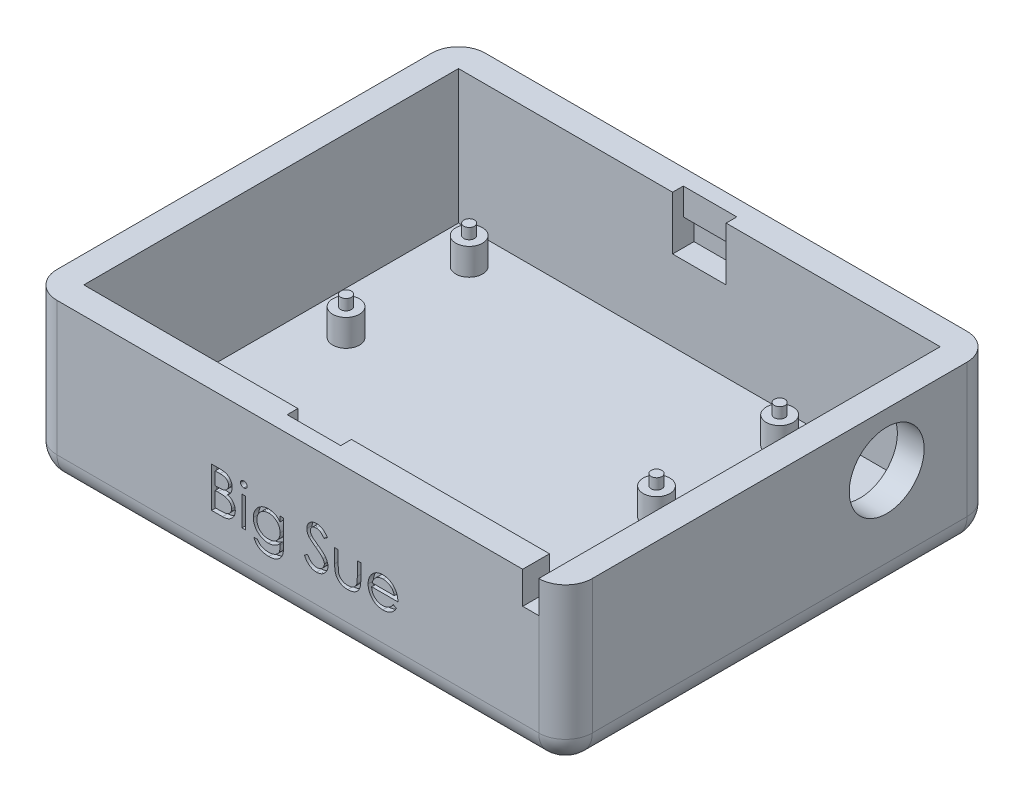
SolidWorks part; units mm, degrees
ref_plane "Front Plane" through (0, 0, 0) normal (0, 0, 1) x (1, 0, 0)
ref_plane "Top Plane" through (0, 0, 0) normal (0, 1, 0) x (1, 0, 0)
ref_plane "Right Plane" through (0, 0, 0) normal (1, 0, 0) x (0, 0, -1)
sketch "Sketch1" plane through (0, 0, 0) normal (0, 1, 0) x (1, 0, 0)
  line L1 (0, 0) -> (100, 0)
  line L2 (0, 0) -> (0, 80)
  line L3 (0, 80) -> (100, 80)
  line L4 (100, 0) -> (100, 80)
  dimension "D1" = 100
  dimension "D2" = 80
extrude "Boss-Extrude1" add sketch "Sketch1" along normal blind 5 contours L3 L4 L1 L2
sketch "Sketch2" plane through (0, 5, 0) normal (0, 1, 0) x (1, 0, 0)
  line L5 (0, 80) -> (100, 80)
  line L6 (0, 80) -> (0, 0)
  line L7 (0, 0) -> (100, 0)
  line L8 (5, 75) -> (5, 5)
  line L9 (5, 5) -> (95, 5)
  line L10 (95, 5) -> (95, 75)
  line L11 (95, 75) -> (5, 75)
  line L12 (5, 75) -> (5, 5)
  line L13 (5, 5) -> (95, 5)
  line L14 (95, 5) -> (95, 75)
  line L15 (95, 75) -> (5, 75)
  line L16 (100, 80) -> (100, 0)
  dimension "D1" = 5
extrude "Boss-Extrude2" add sketch "Sketch2" along normal blind 25
sketch "Sketch3" plane through (100, 0, 0) normal (1, 0, 0) x (0, 0, -1)
  line L0 (80, 30) -> (80, 0) construction
  line L1 (0, 30) -> (80, 30) construction
  circle A0 centre (60, 20) radius 7
  dimension "D1" = 14
  dimension "D2" = 20
  dimension "D3" = 10
extrude "Cut-Extrude1" cut sketch "Sketch3" against normal blind 25
sketch "Sketch4" plane through (0, 5, 0) normal (0, 1, 0) x (1, 0, 0)
  line L0 (5, 75) -> (5, 5) construction
  line L1 (95, 75) -> (5, 75) construction
  circle A0 centre (13, 69) radius 2.5
  dimension "D1" = 8
  dimension "D3" = 5
  dimension "D2" = 6
extrude "Boss-Extrude3" add sketch "Sketch4" along normal blind 5
sketch "Sketch5" plane through (0, 10, 0) normal (0, 1, 0) x (1, 0, 0)
  circle A0 centre (13, 69) radius 1
  circle A1 centre (13, 69) radius 2.5 construction
  dimension "D1" = 2
extrude "Boss-Extrude4" add sketch "Sketch5" along normal blind 2
pattern_linear "LPattern1" count 2 spacing 58 along (1, 0, 0) count 2 spacing 23 along (0, 0, 1) of "Boss-Extrude4", "Boss-Extrude3"
sketch "Sketch7" plane through (0, 0, 0) normal (0, 0, 1) x (1, 0, 0)
  line L0 (0, 30) -> (100, 30) construction
  line L1 (92, 30) -> (95, 30)
  line L2 (92, 30) -> (92, 24)
  line L3 (92, 24) -> (95, 24)
  line L4 (95, 30) -> (95, 24)
  line L5 (100, 30) -> (100, 0) construction
  dimension "D1" = 3
  dimension "D2" = 6
  dimension "D3" = 5
extrude "Cut-Extrude3" cut sketch "Sketch7" against normal blind 5
fillet "Fillet1" radius 5 8 edges at (50, 0, -80) (0, 15, -80) (0, 0, -40) (50, 0, 0) (100, 0, -40) (100, 15, -80) (100, 15, 0) (0, 15, 0)
ref_plane "Plane1" through (50, 0, 0) normal (-1, 0, 0) x (0, 0, 1)
ref_plane "Plane2" through (0, 0, -40) normal (0, 0, 1) x (1, 0, 0)
sketch "Sketch8" plane through (0, 30, 0) normal (0, 1, 0) x (1, 0, 0)
  line L0 (95, 75) -> (5, 75) construction
  line L1 (45, 75) -> (55, 75)
  line L2 (45, 75) -> (45, 77)
  line L3 (45, 77) -> (55, 77)
  line L4 (55, 75) -> (55, 77)
  line L5 (50, 13.75) -> (50, -13.75) construction
  dimension "D1" = 5
  dimension "D2" = 5
  dimension "D3" = 2
extrude "Cut-Extrude4" cut sketch "Sketch8" against normal blind 10
sketch "Sketch9" plane through (0, 0, -77) normal (0, 0, 1) x (1, 0, 0)
  line L0 (55, 20) -> (55, 30) construction
  line L1 (45, 20) -> (55, 20)
  line L2 (45, 20) -> (45, 25)
  line L3 (45, 25) -> (55, 25)
  line L4 (55, 20) -> (55, 25)
extrude "Cut-Extrude5" cut sketch "Sketch9" against normal blind 2
mirror "Mirror1" about plane through (0, 0, -40) normal (0, 0, 1) of "Cut-Extrude5", "Cut-Extrude4"
sketch "Sketch10" plane through (0, 0, 0) normal (0, 0, 1) x (1, 0, 0)
  text T0 "Big Sue " font "Century Gothic" height 7.5
  point P1 (21.0981, 10.4882)
  point P2 (25.295, 9.5966)
  point P3 (24.2177, 8.4995)
  point P4 (23.565, 8.8259)
extrude "Cut-Extrude6" cut sketch "Sketch10" against normal blind 1
